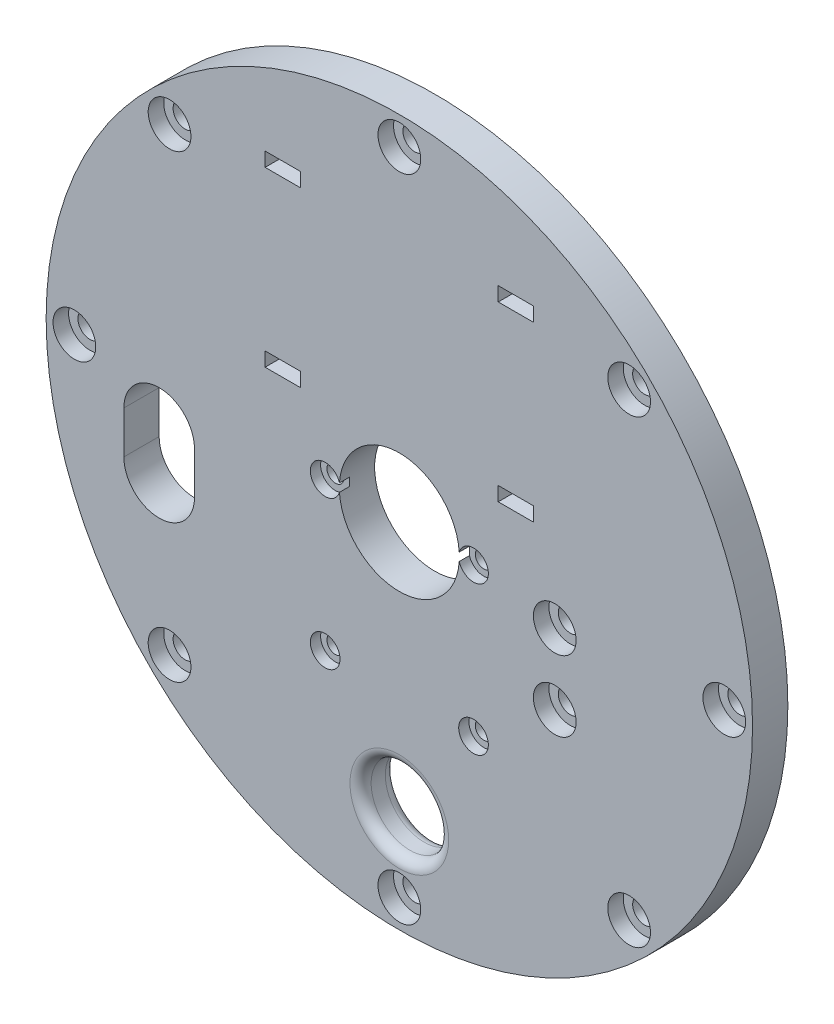
SolidWorks part; units mm, degrees
ref_plane "正面" through (0, 0, 0) normal (0, 0, 1) x (1, 0, 0)
ref_plane "平面" through (0, 0, 0) normal (0, 1, 0) x (1, 0, 0)
ref_plane "右側面" through (0, 0, 0) normal (1, 0, 0) x (0, 0, -1)
sketch "ｽｹｯﾁ1" plane through (0, 0, 0) normal (0, 0, 1) x (1, 0, 0)
  circle A0 centre (0, 0) radius 50
  dimension "D1" = 100
extrude "ﾎﾞｽ - 押し出し1" add sketch "ｽｹｯﾁ1" along normal blind 5
hole_wizard "M2 丸平ねじ用座ぐり穴1" positions "ｽｹｯﾁ2" profile "ｽｹｯﾁ3" counterbore size "M2" standard "JIS" end condition through all
sketch "ｽｹｯﾁ2" plane through (0, 0, 5) normal (0, 0, 1) x (1, 0, 0)
  point P0 (-10.5, 0)
  point P4 (-10.5, -21)
  dimension "D1" = 10.5
  dimension "D2" = 10.5
  dimension "D3" = 21
sketch "ｽｹｯﾁ3" plane through (-10.5, 0, 5) normal (1, 0, 0) x (0, -1, 0)
  line L0 (0, 0) -> (0, 5)
  line L1 (0, 5) -> (1.2, 5)
  line L3 (1.2, 5) -> (1.2, 1.45)
  line L4 (1.2, 1.45) -> (2.1, 1.45)
  line L5 (2.1, 1.45) -> (2.1, 0)
  line L7 (2.1, 0) -> (0, 0)
  line L11 (0, -6.35) -> (0, 107.95) construction
  dimension "通し穴の直径" = 2.4
  dimension "通し穴の深さ" = 5
  dimension "座ぐり穴の直径" = 4.2
  dimension "座ぐり穴の深さ" = 1.45
mirror "ﾐﾗｰ1" about plane through (0, 0, 0) normal (1, 0, 0) of "M2 丸平ねじ用座ぐり穴1"
hole_wizard "M3 丸平ねじ用座ぐり穴2" positions "ｽｹｯﾁ4" profile "ｽｹｯﾁ5" counterbore size "M3" standard "JIS" end condition through all
sketch "ｽｹｯﾁ4" plane through (0, 0, 5) normal (0, 0, 1) x (1, 0, 0)
  point P0 (46, 0)
  point P2 (46, 0)
  dimension "D1" = 46
sketch "ｽｹｯﾁ5" plane through (46, 0, 5) normal (1, 0, 0) x (0, -1, 0)
  line L0 (0, 0) -> (0, 5)
  line L1 (0, 5) -> (1.7, 5)
  line L3 (1.7, 5) -> (1.7, 2.2)
  line L4 (1.7, 2.2) -> (3.025, 2.2)
  line L5 (3.025, 2.2) -> (3.025, 0)
  line L7 (3.025, 0) -> (0, 0)
  line L11 (0, -6.35) -> (0, 107.95) construction
  dimension "通し穴の直径" = 3.4
  dimension "通し穴の深さ" = 5
  dimension "座ぐり穴の直径" = 6.05
  dimension "座ぐり穴の深さ" = 2.2
pattern_circular "円形ﾊﾟﾀｰﾝ1" count 8 every 45 about axis through (0, 0, 0) along (0, 0, 1) of "M3 丸平ねじ用座ぐり穴2"
sketch "ｽｹｯﾁ6" plane through (0, 0, 5) normal (0, 0, 1) x (1, 0, 0)
  circle A0 centre (0, 0) radius 8.5
  dimension "D1" = 17
extrude "ｶｯﾄ - 押し出し1" cut sketch "ｽｹｯﾁ6" against normal through all
sketch "ｽｹｯﾁ7" plane through (0, 0, 5) normal (0, 0, 1) x (1, 0, 0)
  line L0 (0, -40.975) -> (0, -42.975) construction
  line L1 (0, 0) -> (0, -30) construction
  circle A0 centre (0, -35.4875) radius 5.4875
  circle A1 centre (0, -46) radius 3.025 construction
  dimension "D1" = 30
  dimension "D2" = 2
extrude "ｶｯﾄ - 押し出し2" cut sketch "ｽｹｯﾁ7" against normal through all
fillet "ﾌｨﾚｯﾄ1" radius 1.5 2 edges at (5.4875, -35.4875, 5) (5.4875, -35.4875, 0)
hole_wizard "M3 丸平ねじ用座ぐり穴3" positions "ｽｹｯﾁ9" profile "ｽｹｯﾁ10" counterbore size "M3" standard "JIS" end condition through all
sketch "ｽｹｯﾁ9" plane through (0, 0, 5) normal (0, 0, 1) x (1, 0, 0)
  point P0 (22, -2)
  point P4 (22, -12)
  point P7 (0, 0)
  dimension "D1" = 22
  dimension "D2" = 2
  dimension "D3" = 10
sketch "ｽｹｯﾁ10" plane through (22, -2, 5) normal (1, 0, 0) x (0, -1, 0)
  line L0 (0, 0) -> (0, 5)
  line L1 (0, 5) -> (1.7, 5)
  line L3 (1.7, 5) -> (1.7, 2.2)
  line L4 (1.7, 2.2) -> (3.025, 2.2)
  line L5 (3.025, 2.2) -> (3.025, 0)
  line L7 (3.025, 0) -> (0, 0)
  line L11 (0, -6.35) -> (0, 107.95) construction
  dimension "通し穴の直径" = 3.4
  dimension "通し穴の深さ" = 5
  dimension "座ぐり穴の直径" = 6.05
  dimension "座ぐり穴の深さ" = 2.2
sketch "ｽｹｯﾁ11" plane through (0, 0, 0) normal (0, 0, -1) x (-1, 0, 0)
  line L1 (-24, 11.5) -> (24, 11.5)
  line L2 (-24, 11.5) -> (-24, 34)
  line L3 (-24, 34) -> (24, 34)
  line L4 (24, 11.5) -> (24, 34)
  point P4 (0, 11.5)
  dimension "D1" = 11.5
  dimension "D2" = 48
  dimension "D3" = 22.5
sketch "ｽｹｯﾁ12" plane through (0, 0, 0) normal (0, 0, -1) x (-1, 0, 0)
  line L0 (-24, 34) -> (24, 34) construction
  line L11 (-24, 11.5) -> (24, 11.5) construction
  line L12 (19, 36) -> (14, 36)
  line L13 (19, 36) -> (19, 34)
  line L14 (19, 34) -> (14, 34)
  line L15 (14, 36) -> (14, 34)
  line L16 (19, 11.5) -> (14, 11.5)
  line L17 (19, 11.5) -> (19, 9.5)
  line L18 (19, 9.5) -> (14, 9.5)
  line L19 (14, 11.5) -> (14, 9.5)
  line L20 (24, 11.5) -> (24, 34) construction
  dimension "D4" = 5
  dimension "D5" = 2
  dimension "D6" = 5
extrude "ｶｯﾄ - 押し出し4" cut sketch "ｽｹｯﾁ12" against normal through all
sketch "ｽｹｯﾁ14" plane through (0, 0, 0) normal (0, 0, -1) x (-1, 0, 0)
  line L11 (24, 11.5) -> (24, 34) construction
  line L12 (24, 32) -> (26, 32)
  line L13 (24, 32) -> (24, 27)
  line L14 (24, 27) -> (26, 27)
  line L15 (26, 32) -> (26, 27)
  line L16 (26, 27) -> (26, 18.5) construction
  line L17 (24, 18.5) -> (26, 18.5)
  line L18 (24, 18.5) -> (24, 13.5)
  line L19 (24, 13.5) -> (26, 13.5)
  line L20 (26, 18.5) -> (26, 13.5)
  line L21 (-24, 34) -> (24, 34) construction
  point P0 (24, 22.75)
  point P1 (26, 22.75)
  dimension "D1" = 2
  dimension "D2" = 5
  dimension "D3" = 2
extrude "ﾎﾞｽ - 押し出し2" add sketch "ｽｹｯﾁ14" along normal blind 3
fillet "ﾌｨﾚｯﾄ2" radius 1 2 edges at (-26, 16, 0) (-26, 29.5, 0)
mirror "ﾐﾗｰ2" about plane through (0, 0, 0) normal (1, 0, 0) of "ｶｯﾄ - 押し出し4", "ﾌｨﾚｯﾄ2", "ﾎﾞｽ - 押し出し2"
sketch "ｽｹｯﾁ15" plane through (0, 0, 5) normal (0, 0, 1) x (1, 0, 0)
  line L0 (-34, -5.5) -> (-34, -11.5) construction
  line L1 (-29, -5.5) -> (-29, -11.5)
  line L2 (-39, -5.5) -> (-39, -11.5)
  line L3 (-34, -0.5) -> (-34, -16.5) construction
  arc A0 (-29, -5.5) -> (-39, -5.5) centre (-34, -5.5) ccw
  arc A1 (-39, -11.5) -> (-29, -11.5) centre (-34, -11.5) ccw
  point P2 (-34, -8.5)
  point P7 (0, 0)
  dimension "D1" = 29
  dimension "D2" = 5.5
  dimension "D3" = 10
  dimension "D4" = 16
extrude "ｶｯﾄ - 押し出し5" cut sketch "ｽｹｯﾁ15" against normal through all
